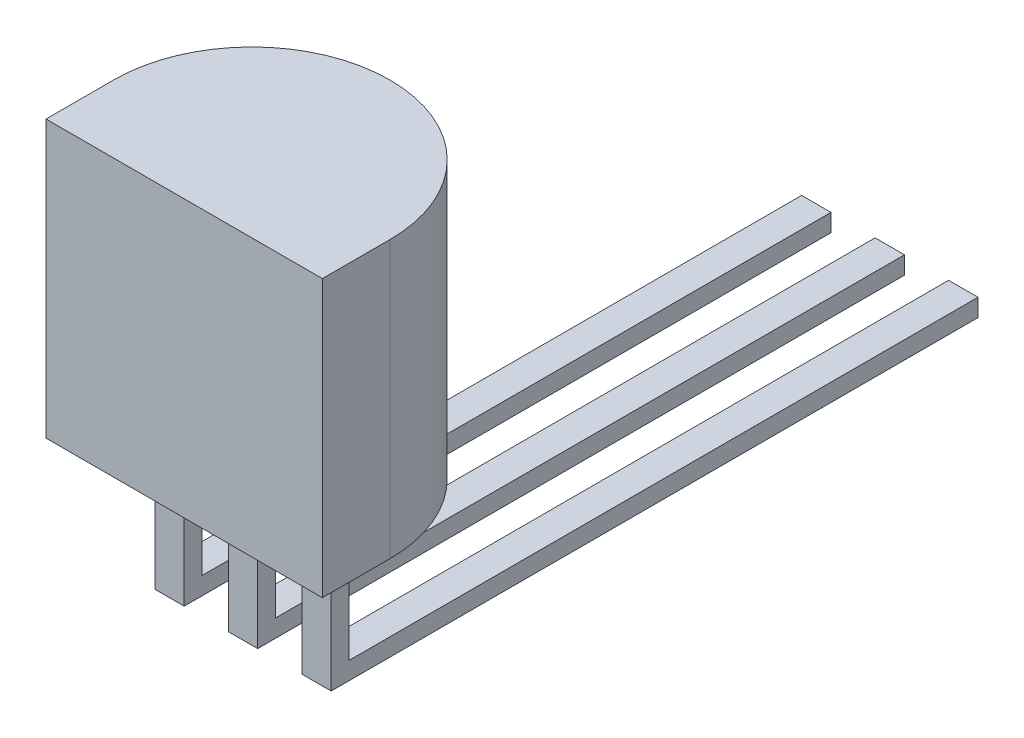
SolidWorks part; units mm, degrees
ref_plane "前视基准面" through (0, 0, 0) normal (0, 0, 1) x (1, 0, 0)
ref_plane "上视基准面" through (0, 0, 0) normal (0, 1, 0) x (1, 0, 0)
ref_plane "右视基准面" through (0, 0, 0) normal (1, 0, 0) x (0, 0, -1)
sketch "草图1" plane through (0, 0, 0) normal (0, 1, 0) x (1, 0, 0)
  line L0 (-2.35, 0) -> (2.35, 0)
  line L1 (-2.35, 0) -> (-2.35, 1.15)
  line L2 (0, -9.9847) -> (0, 31.9184) construction
  line L3 (2.35, 0) -> (2.35, 1.15)
  line L4 (2.5443, 3.5) -> (-3.4027, 3.5) construction
  line L5 (-4.1666, 1.15) -> (5.1384, 1.15) construction
  arc A0 (2.35, 1.15) -> (-2.35, 1.15) centre (0, 1.15) ccw
  dimension "D1" = 4.7
  dimension "D2" = 3.5
extrude "凸台-拉伸1" add sketch "草图1" along normal blind 4.7
sketch "草图2" plane through (0, 0, 0) normal (0, -1, 0) x (1, 0, 0)
  line L0 (-2.8551, -1.15) -> (2.9269, -1.15) construction
  line L1 (0, 0.5568) -> (0, -3.9133) construction
  line L2 (1, -1) -> (1.5, -1)
  line L3 (-0.25, -1) -> (0.25, -1)
  line L4 (-0.25, -1) -> (-0.25, -1.3)
  line L5 (-0.25, -1.3) -> (0.25, -1.3)
  line L6 (0.25, -1) -> (0.25, -1.3)
  line L7 (1, -1) -> (1, -1.3)
  line L8 (1, -1.3) -> (1.5, -1.3)
  line L9 (1.5, -1) -> (1.5, -1.3)
  line L10 (-1.5, -1) -> (-1.5, -1.3)
  line L11 (-1, -1.3) -> (-1.5, -1.3)
  line L12 (-1, -1) -> (-1, -1.3)
  line L13 (-1, -1) -> (-1.5, -1)
  dimension "D1" = 0.5
  dimension "D2" = 0.3
  dimension "D3" = 2
extrude "凸台-拉伸2" add sketch "草图2" along normal blind 2
sketch "草图3" plane through (0, 0, -1) normal (0, 0, 1) x (1, 0, 0)
  line L0 (0.25, -2) -> (0.25, 0) construction
  line L1 (-0.25, -2) -> (0.25, -2)
  line L2 (-0.25, -2) -> (-0.25, -2.3)
  line L3 (-0.25, -2.3) -> (0.25, -2.3)
  line L4 (0.25, -2) -> (0.25, -2.3)
  line L5 (-1, -2) -> (-1, 0) construction
  line L6 (-1.5, -2) -> (-1, -2)
  line L7 (-1.5, -2) -> (-1.5, -2.3)
  line L8 (-1.5, -2.3) -> (-1, -2.3)
  line L9 (-1, -2) -> (-1, -2.3)
  line L10 (1.5, -2) -> (1.5, 0) construction
  line L11 (1, -2) -> (1.5, -2)
  line L12 (1, -2) -> (1, -2.3)
  line L13 (1, -2.3) -> (1.5, -2.3)
  line L14 (1.5, -2) -> (1.5, -2.3)
  dimension "D1" = 0.3
extrude "凸台-拉伸3" add sketch "草图3" against normal blind 11
